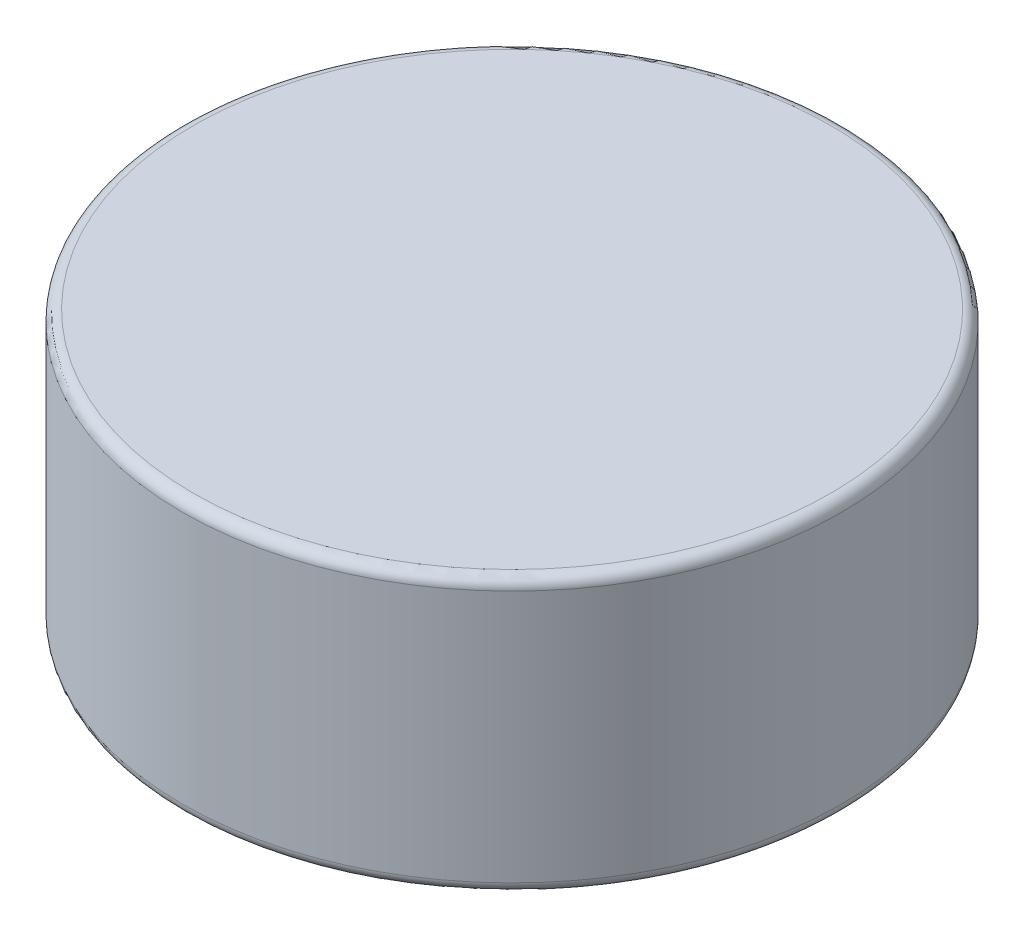
SolidWorks part; units mm, degrees
ref_plane "Front Plane" through (0, 0, 0) normal (0, 0, 1) x (1, 0, 0)
ref_plane "Top Plane" through (0, 0, 0) normal (0, 1, 0) x (1, 0, 0)
ref_plane "Right Plane" through (0, 0, 0) normal (1, 0, 0) x (0, 0, -1)
sketch "Sketch1" plane through (0, 0, 0) normal (0, 1, 0) x (1, 0, 0)
  circle A0 centre (0, 0) radius 3
  dimension "D1" = 6
extrude "Boss-Extrude1" add sketch "Sketch1" along normal mid plane 2.5
fillet "Fillet1" radius 0.1 2 edges at (0, -1.25, 3) (0, 1.25, 3)
